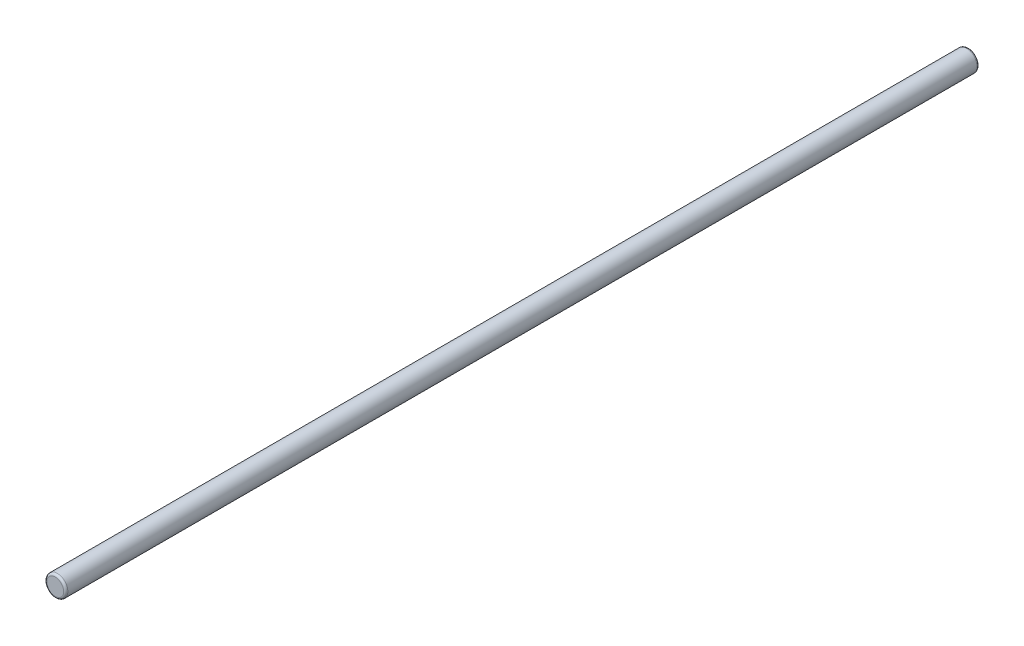
SolidWorks part; units mm, degrees
ref_plane "Face" through (0, 0, 0) normal (0, 0, 1) x (1, 0, 0)
ref_plane "Dessus" through (0, 0, 0) normal (0, 1, 0) x (1, 0, 0)
ref_plane "Droite" through (0, 0, 0) normal (1, 0, 0) x (0, 0, -1)
sketch "Esquisse1" plane through (0, 0, 0) normal (1, 0, 0) x (0, 0, -1)
  line L0 (0, 0) -> (0, 1)
  line L1 (0, 1) -> (87, 1)
  line L2 (87, 1) -> (87, 0)
  line L3 (0, 0) -> (108.1391, 0) construction
  line L4 (0, 0) -> (87, 0)
  point P3 (0, 1)
  dimension "D1" = 87
revolve "Révolution1" add sketch "Esquisse1" angle 360 about L3
fillet "Congé1" radius 0.2 1 edges at (1, 0, -87)
fillet "Congé2" radius 0.2 1 edges at (1, 0, 0)
